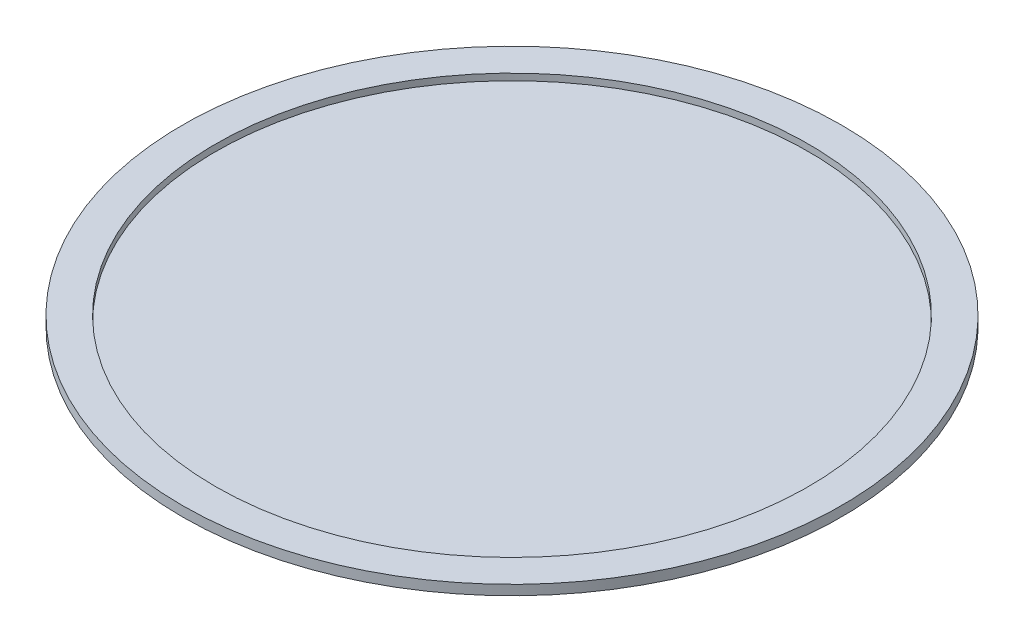
SolidWorks part; units mm, degrees
material "6061-T6 (SS)"
ref_plane "Front Plane" through (0, 0, 0) normal (0, 0, 1) x (1, 0, 0)
ref_plane "Top Plane" through (0, 0, 0) normal (0, 1, 0) x (1, 0, 0)
ref_plane "Right Plane" through (0, 0, 0) normal (1, 0, 0) x (0, 0, -1)
sketch "Sketch1" plane through (0, 0, 0) normal (0, 1, 0) x (1, 0, 0)
  circle A0 centre (0, 0) radius 100
  dimension "D1" = 200
extrude "Boss-Extrude1" add sketch "Sketch1" along normal blind 3 contours A0
sketch "Sketch2" plane through (0, 3, 0) normal (0, 1, 0) x (1, 0, 0)
  circle A0 centre (0, 0) radius 90
  circle A1 centre (0, 0) radius 100 construction
  dimension "D1" = 10
extrude "Cut-Extrude1" cut sketch "Sketch2" against normal blind 2
